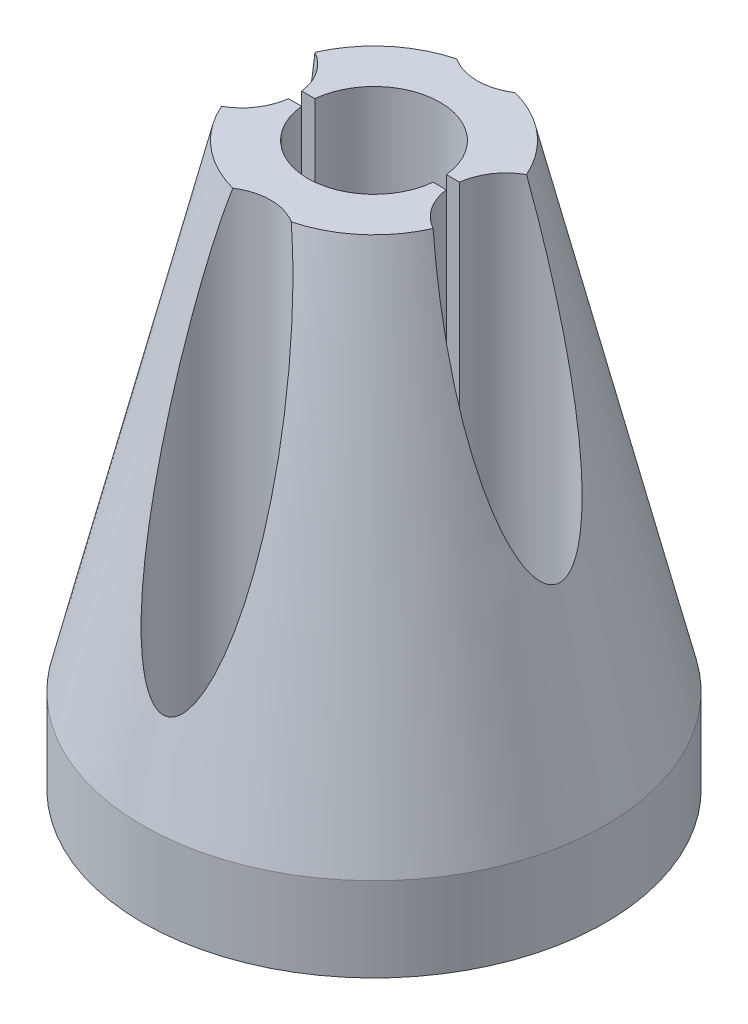
SolidWorks part; units mm, degrees
ref_plane "前视基准面" through (0, 0, 0) normal (0, 0, 1) x (1, 0, 0)
ref_plane "上视基准面" through (0, 0, 0) normal (0, 1, 0) x (1, 0, 0)
ref_plane "右视基准面" through (0, 0, 0) normal (1, 0, 0) x (0, 0, -1)
other "Configuration Table"
sketch "草图1" plane through (0, 0, 0) normal (0, 0, 1) x (1, 0, 0)
  line L0 (0, 0) -> (0, 29)
  line L1 (0, 29) -> (7, 29)
  line L2 (7, 29) -> (14, 0.1)
  line L3 (14, 0) -> (0, 0)
  line L4 (14, 0.1) -> (14, 0)
  line L5 (4, 29) -> (4, 0)
  dimension "D1" = 7
  dimension "D2" = 14
  dimension "D3" = 0.1
  dimension "D4" = 29
  dimension "D5" = 4
revolve "旋转1" add sketch "草图1" angle 360 about L0
sketch "草图2" plane through (0, 0, 0) normal (0, -1, 0) x (1, 0, 0)
  line L1 (7, 0) -> (14, 0) construction
  circle A2 centre (8, 0) radius 1.6
  circle A3 centre (0, 9.5) radius 1.6
  circle A4 centre (0, -9.5) radius 1.6
  circle A5 centre (-8, 0) radius 1.6
  point P12 (0, 0)
  point P15 (0, 0)
  dimension "D1" = 3.2
  dimension "D2" = 8
  dimension "D3" = 3.2
  dimension "D4" = 9.5
  dimension "D5" = 2
  dimension "D6" = 2
extrude "切除-拉伸1" cut sketch "草图2" against normal through all
sketch "草图3" plane through (0, 0, 0) normal (0, -1, 0) x (1, 0, 0)
  circle A0 centre (0, 9.5) radius 3.25
  circle A1 centre (8, 0) radius 3.25
  circle A2 centre (0, -9.5) radius 3.25
  circle A3 centre (-8, 0) radius 3.25
  dimension "D1" = 6.5
  dimension "D2" = 6.5
  dimension "D3" = 6.5
  dimension "D4" = 6.5
sketch "草图5" plane through (0, 0, 0) normal (0, -1, 0) x (1, 0, 0)
  circle A0 centre (0, 0) radius 4
  circle A1 centre (0, 0) radius 3.3264
extrude "凸台-拉伸1" add sketch "草图5" against normal blind 0.3
sketch "草图6" plane through (0, 0, 0) normal (0, -1, 0) x (1, 0, 0)
  circle A0 centre (0, 0) radius 3.3264 construction
  circle A1 centre (0, 0) radius 14
  circle A2 centre (0, 0) radius 14
  circle A3 centre (0, 0) radius 3.3264
  circle A4 centre (0, 9.5) radius 1.6 construction
  circle A5 centre (0, 9.5) radius 1.6
  circle A6 centre (-8, 0) radius 1.6 construction
  circle A7 centre (-8, 0) radius 1.6
  circle A8 centre (8, 0) radius 1.6 construction
  circle A9 centre (8, 0) radius 1.6
  circle A10 centre (0, -9.5) radius 1.6 construction
  circle A11 centre (0, -9.5) radius 1.6
  dimension "D1" = 0
extrude "凸台-拉伸2" add sketch "草图6" along normal blind 5
extrude "切除-拉伸5" cut sketch "草图3" against normal through all from offset 1
sketch "草图7" plane through (0, 0.3, 0) normal (0, 1, 0) x (1, 0, 0)
  circle A1 centre (0, 0) radius 3.3264 construction
  circle A2 centre (0, 0) radius 4
  circle A3 centre (0, 0) radius 4
  circle A4 centre (0, 0) radius 3.3264
  dimension "D1" = 0
extrude "切除-拉伸6" cut sketch "草图7" against normal blind 4
sketch "草图8" plane through (0, 29, 0) normal (0, 1, 0) x (1, 0, 0)
  line L1 (-6, -0.4) -> (6, -0.4)
  line L2 (-6, -0.4) -> (-6, 0.4)
  line L3 (-6, 0.4) -> (6, 0.4)
  line L4 (6, -0.4) -> (6, 0.4)
  line L5 (-6, -0.4) -> (6, 0.4) construction
  line L6 (-6, 0.4) -> (6, -0.4) construction
  point P0 (0, 0)
  dimension "D1" = 12
  dimension "D2" = 0.8
extrude "切除-拉伸7" cut sketch "草图8" against normal up to surface (30 mm away) up to face at (8, -1, -3.25)
